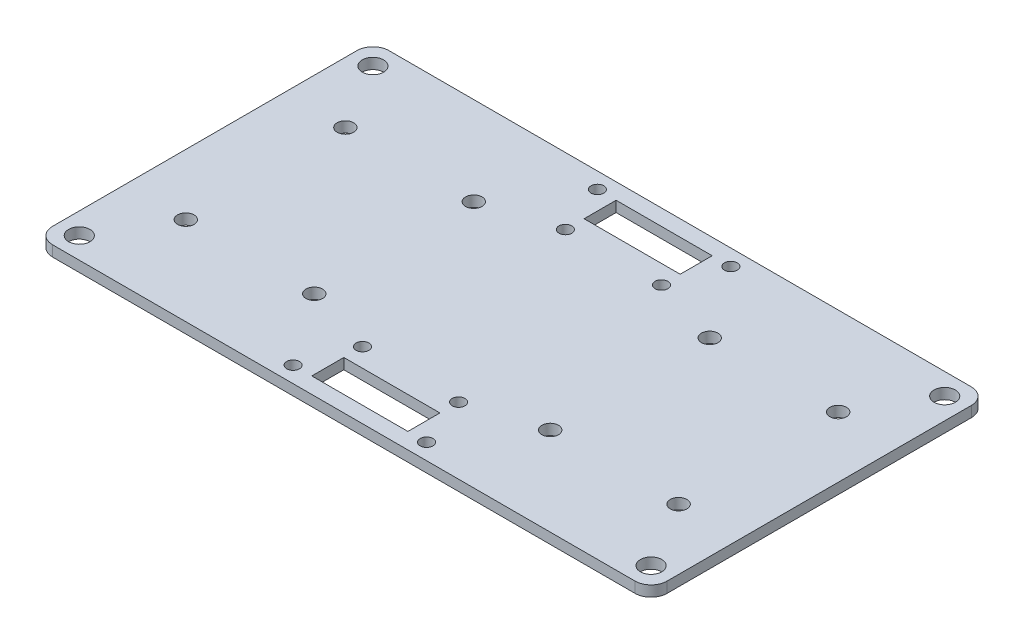
SolidWorks part; units mm, degrees
ref_plane "Plano frontal" through (0, 0, 0) normal (0, 0, 1) x (1, 0, 0)
ref_plane "Plano superior" through (0, 0, 0) normal (0, 1, 0) x (1, 0, 0)
ref_plane "Plano direito" through (0, 0, 0) normal (1, 0, 0) x (0, 0, -1)
sketch "Esboço1" plane through (0, 0, 0) normal (0, 1, 0) x (1, 0, 0)
  line L7 (-57.5484, 31.5) -> (57.5484, 31.5)
  line L8 (57.5484, 31.5) -> (57.5484, -31.5)
  line L9 (57.5484, -31.5) -> (-57.5484, -31.5)
  line L10 (-57.5484, -31.5) -> (-57.5484, 31.5)
  line L11 (0, 31.5) -> (0, -31.5) construction
  line L12 (-57.5484, 0) -> (57.5484, 0) construction
  dimension "D1" = 63
  dimension "D2" = 115.0968
extrude "Ressalto-extrusão1" add sketch "Esboço1" along normal blind 2
sketch "Esboço2" plane through (0, 2, 0) normal (0, 1, 0) x (1, 0, 0)
  line L0 (-57.5484, 0) -> (57.5484, 0) construction
  line L1 (-57.5484, 31.5) -> (-57.5484, -31.5) construction
  line L2 (-57.5484, -31.5) -> (57.5484, -31.5) construction
  line L5 (57.5484, -31.5) -> (57.5484, 31.5) construction
  line L6 (0, -31.5) -> (0, 31.5) construction
  line L7 (57.5484, 31.5) -> (-57.5484, 31.5) construction
  circle A8 centre (-46.1536, -14.945) radius 1.55
  circle A10 centre (-22.0936, -14.94) radius 1.55
  circle A11 centre (22.0936, -14.94) radius 1.55
  circle A12 centre (46.1536, -14.945) radius 1.55
  circle A13 centre (46.1536, 14.945) radius 1.55
  circle A14 centre (22.0936, 14.94) radius 1.55
  circle A15 centre (-22.0936, 14.94) radius 1.55
  circle A16 centre (-46.1536, 14.945) radius 1.55
  dimension "D1" = 16.555
  dimension "D3" = 3.1
  dimension "D4" = 16.56
  dimension "D2" = 24.06
  dimension "D5" = 11.3948
extrude "Corte-extrusão1" cut sketch "Esboço2" against normal through all
sketch "Esboço3" plane through (0, 0, 0) normal (0, -1, 0) x (1, 0, 0)
  line L0 (0, 31.5) -> (0, 28.5) construction
  line L1 (-57.5484, 31.5) -> (57.5484, 31.5) construction
  line L2 (-9, 28.5) -> (9, 28.5)
  line L3 (9, 28.5) -> (9, 22.5)
  line L4 (-9, 28.5) -> (-9, 22.5)
  line L5 (-9, 22.5) -> (9, 22.5)
  line L6 (-57.5484, 0) -> (57.5484, 0) construction
  line L7 (-57.5484, -31.5) -> (-57.5484, 31.5) construction
  line L8 (57.5484, 31.5) -> (57.5484, -31.5) construction
  line L9 (9, 28.5) -> (9, 22.5)
  line L10 (-9, 28.5) -> (-9, 22.5)
  line L11 (9, 28.5) -> (9, 22.5)
  line L12 (-9, 28.5) -> (-9, 22.5)
  line L13 (9, 28.5) -> (9, 22.5)
  line L14 (-9, 28.5) -> (-9, 22.5)
  line L15 (0, -31.5) -> (0, -28.5) construction
  line L16 (-9, -28.5) -> (-9, -22.5)
  line L17 (9, -28.5) -> (9, -22.5)
  line L18 (-9, -28.5) -> (-9, -22.5)
  line L19 (9, -28.5) -> (9, -22.5)
  line L20 (-9, -28.5) -> (-9, -22.5)
  line L21 (9, -28.5) -> (9, -22.5)
  line L22 (-9, -22.5) -> (9, -22.5)
  line L23 (-9, -28.5) -> (-9, -22.5)
  line L24 (9, -28.5) -> (9, -22.5)
  line L25 (-9, -28.5) -> (9, -28.5)
  point P8 (0, 28.5)
  point P22 (0, -28.5)
  dimension "D1" = 3
  dimension "D2" = 18
  dimension "D3" = 6
extrude "Corte-extrusão2" cut sketch "Esboço3" against normal through all contours L4 L5 L3 L2 | L16 L25 L17 L22
sketch "Esboço5" plane through (0, 2, 0) normal (0, 1, 0) x (1, 0, 0)
  line L2 (57.5484, 31.5) -> (-57.5484, 31.5) construction
  line L3 (57.5484, -31.5) -> (57.5484, 31.5) construction
  line L4 (57.5484, 0) -> (-57.5484, 0) construction
  line L5 (-57.5484, 31.5) -> (-57.5484, -31.5) construction
  line L6 (0, 31.5) -> (0, -31.5) construction
  line L7 (-57.5484, -31.5) -> (57.5484, -31.5) construction
  line L8 (53.5484, -13.175) -> (53.5484, -27.5) construction
  line L9 (-53.5484, -13.175) -> (-53.5484, -27.5) construction
  line L10 (-53.5484, 21.175) -> (-53.5484, 35.5) construction
  circle A0 centre (53.5484, 27.5) radius 2
  circle A1 centre (53.5484, -27.5) radius 2
  circle A2 centre (-53.5484, -27.5) radius 2
  circle A3 centre (-53.5484, 27.5) radius 2
  dimension "D2" = 4
  dimension "D1" = 4
  dimension "D3" = 4
extrude "Corte-extrusão3" cut sketch "Esboço5" against normal through all
fillet "Filete1" radius 3 4 edges at (57.5484, 1, -31.5) (57.5484, 1, 31.5) (-57.5484, 1, 31.5) (-57.5484, 1, -31.5)
sketch "Esboço8" plane through (0, 2, 0) normal (0, 1, 0) x (1, 0, 0)
  line L0 (-57.5484, 28.5) -> (-57.5484, -28.5) construction
  line L1 (54.5484, 31.5) -> (-54.5484, 31.5) construction
  line L2 (0, 0) -> (0, 31.5) construction
  line L3 (57.5484, 0) -> (-57.5484, 0) construction
  line L4 (-54.5484, -31.5) -> (54.5484, -31.5) construction
  line L5 (57.5484, -28.5) -> (57.5484, 28.5) construction
  circle A0 centre (-12.4984, 28.5) radius 1.2
  circle A1 centre (12.4984, 28.5) radius 1.2
  circle A2 centre (12.4984, -28.5) radius 1.2
  circle A3 centre (-12.4984, -28.5) radius 1.2
  circle A8 centre (-8.9984, -19) radius 1.2
  circle A12 centre (8.9984, -19) radius 1.2
  circle A13 centre (8.9984, 19) radius 1.2
  circle A14 centre (-8.9984, 19) radius 1.2
  dimension "D1" = 2.4
  dimension "D4" = 2.4
  dimension "D5" = 12.5
  dimension "D6" = 48.55
  dimension "D2" = 45.05
  dimension "D3" = 3
extrude "Corte-extrusão4" cut sketch "Esboço8" against normal through all
